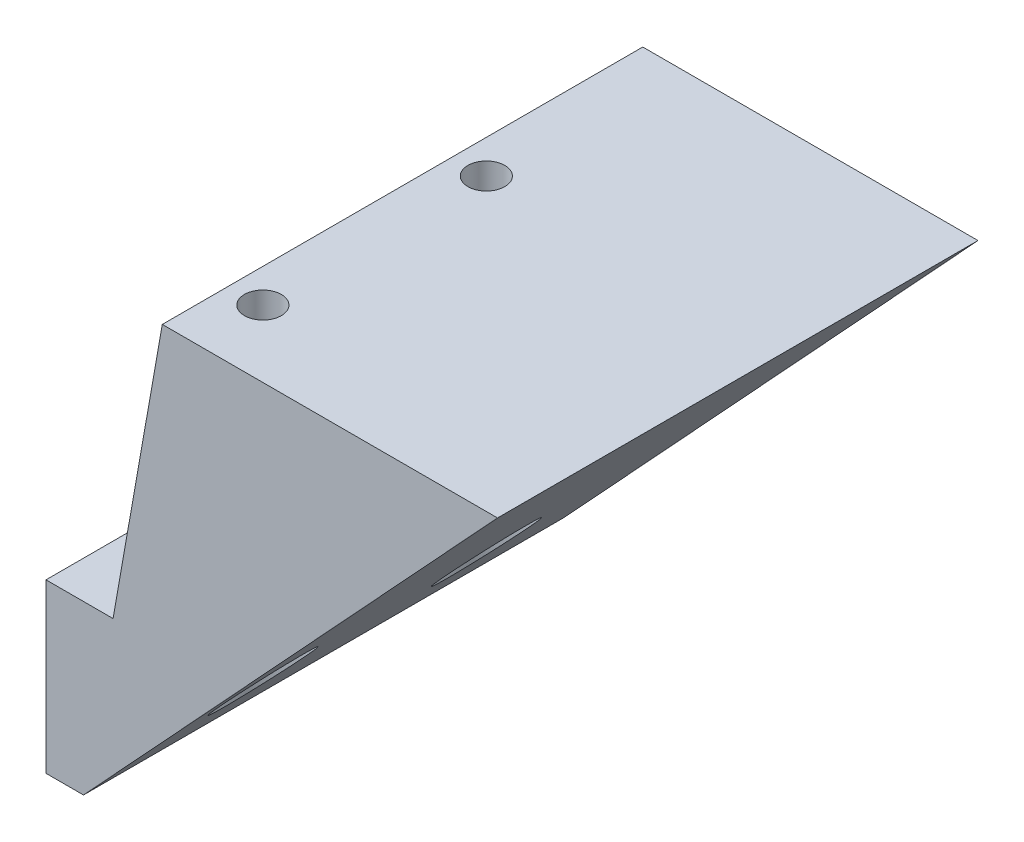
SolidWorks part; units mm, degrees
ref_plane "前视基准面" through (0, 0, 0) normal (0, 0, 1) x (1, 0, 0)
ref_plane "上视基准面" through (0, 0, 0) normal (0, 1, 0) x (1, 0, 0)
ref_plane "右视基准面" through (0, 0, 0) normal (1, 0, 0) x (0, 0, -1)
other "Configuration Table"
sketch "草图1" plane through (0, 0, 0) normal (0, 0, 1) x (1, 0, 0)
  line L0 (0, 0) -> (7.0531, 40)
  line L1 (7.0531, 40) -> (37.0531, 40)
  line L2 (37.0531, 40) -> (0, 0)
  dimension "D1" = 100
  dimension "D2" = 30
  dimension "D3" = 40
extrude "凸台-拉伸1" add sketch "草图1" along normal blind 43
sketch "草图2" plane through (0, 40, 0) normal (0, 1, 0) x (1, 0, 0)
  line L0 (37.0531, 0) -> (7.0531, 0) construction
  line L1 (7.0531, -43) -> (7.0531, 0) construction
  circle A0 centre (10.0531, -17) radius 1.65
  circle A1 centre (10.0531, -37) radius 1.65
  point P8 (0, 0)
  dimension "D1" = 3.3
  dimension "D2" = 20
  dimension "D3" = 17
  dimension "D4" = 3
extrude "切除-拉伸1" cut sketch "草图2" against normal blind 40
sketch "草图3" plane through (0, 0, 43) normal (0, 0, 1) x (1, 0, 0)
  line L0 (2.6449, 15) -> (-3.3551, 15)
  line L1 (7.0531, 40) -> (0, 0) construction
  line L2 (-3.3551, 15) -> (-3.3551, 0)
  line L3 (-3.3551, 0) -> (0, 0)
  line L4 (2.6449, 15) -> (0, 0)
  dimension "D1" = 6
  dimension "D2" = 15
extrude "凸台-拉伸2" add sketch "草图3" against normal blind 43
sketch "草图4" plane through (0, 0, 0) normal (0, -1, 0) x (1, 0, 0)
  circle A0 centre (10.0531, 37) radius 3.5
  circle A1 centre (10.0531, 17) radius 3.5
  dimension "D1" = 7
  dimension "D2" = 7
extrude "切除-拉伸2" cut sketch "草图4" against normal blind 15
